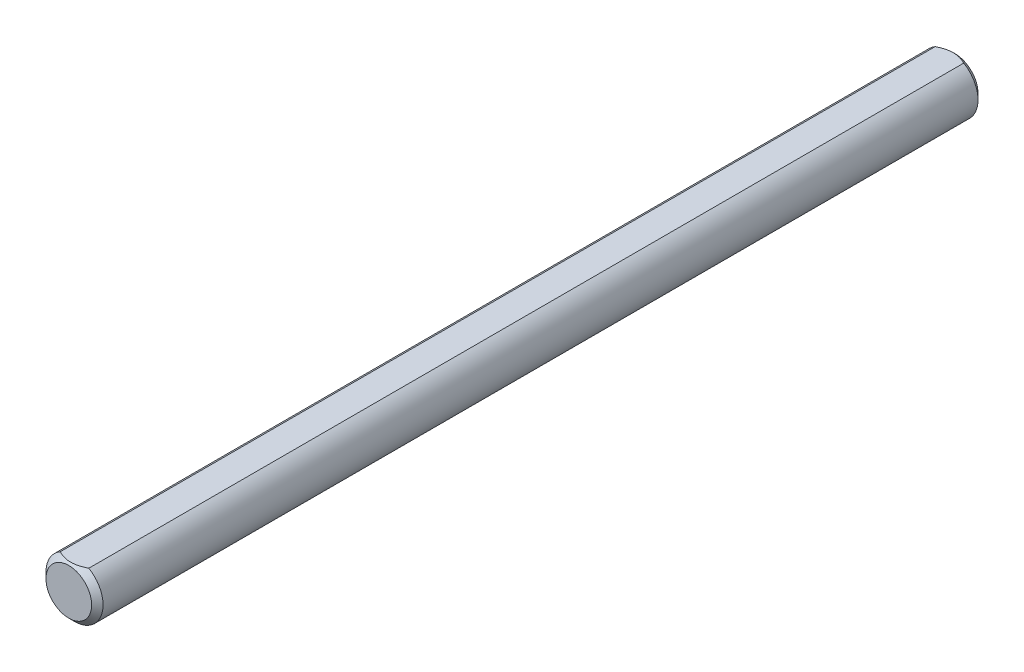
SolidWorks part; units mm, degrees
ref_plane "Front" through (0, 0, 0) normal (0, 0, 1) x (1, 0, 0)
ref_plane "Top" through (0, 0, 0) normal (0, 1, 0) x (1, 0, 0)
ref_plane "Right" through (0, 0, 0) normal (1, 0, 0) x (0, 0, -1)
sketch "Sketch1" plane through (0, 0, 0) normal (0, 0, 1) x (1, 0, 0)
  circle A0 centre (0, 0) radius 3.175
  dimension "D1" = 6.35
extrude "Extrude1" add sketch "Sketch1" along normal mid plane 98.552
chamfer "Chamfer1" distance 0.635 angle 45 2 edges at (3.175, 0, -49.276) (3.175, 0, 49.276)
sketch "Sketch13" plane through (0, 0, 0) normal (0, 0, 1) x (1, 0, 0)
  line L3 (-1.5875, 2.7496) -> (1.5875, 2.7496)
  circle A0 centre (0, 0) radius 3.175 construction
  arc A1 (1.5875, 2.7496) -> (-1.5875, 2.7496) centre (0, 0) ccw
  dimension "D1" = 3.175
extrude "Extrude7" cut sketch "Sketch13" against normal through all and the other way through all
equation "\"D1@Chamfer1\" = \"D1@Sketch1\" * .1"
equation "\"D1@Sketch13\" = \"D1@Sketch1\" * .5"
